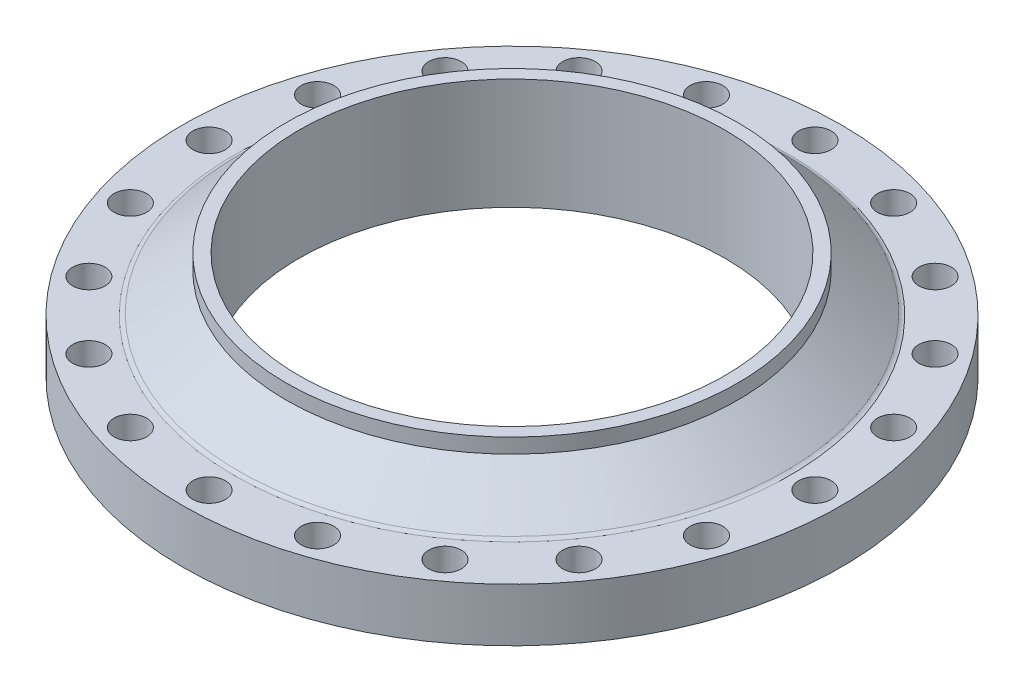
SolidWorks part; units mm, degrees
ref_plane "Front Plane" through (0, 0, 0) normal (0, 0, 1) x (1, 0, 0)
ref_plane "Top Plane" through (0, 0, 0) normal (0, 1, 0) x (1, 0, 0)
ref_plane "Right Plane" through (0, 0, 0) normal (1, 0, 0) x (0, 0, -1)
sketch "Sketch1" plane through (0, 0, 0) normal (0, 0, 1) x (1, 0, 0)
  line L0 (0, 92.0971) -> (0, -93.3251) construction
  line L1 (287.4, 0) -> (370, 0)
  line L2 (370, 0) -> (375, 5)
  line L3 (375, 5) -> (445, 5)
  line L4 (445, 5) -> (445, 77)
  line L5 (445, 77) -> (375, 77)
  line L6 (0, 92.0971) -> (0, 282.9763) construction
  line L7 (287.4, 0) -> (287.4, 150)
  line L9 (287.4, 150) -> (304.8, 150)
  line L10 (304.8, 150) -> (304.8, 130)
  line L11 (375, 77) -> (376.7318, 88.8744)
  line L12 (304.8, 130) -> (369.3298, 79.4292)
  arc A1 (375, 77) -> (369.3298, 79.4292) centre (376.7318, 88.8744) cw
  dimension "D1" = 150
  dimension "D2" = 72
  dimension "D3" = 5
  dimension "D4" = 17.4
  dimension "D5" = 20
  dimension "D7" = 12
revolve "Revolve2" add sketch "Sketch1" angle 360 about L6
sketch "Sketch2" plane through (0, 0, 0) normal (0, 1, 0) x (1, 0, 0)
  line L1 (0, 0) -> (409, 0) construction
  circle A0 centre (409, 0) radius 22
  circle A1 centre (388.9821, -126.388) radius 22
  circle A2 centre (330.888, -240.4042) radius 22
  circle A3 centre (240.4042, -330.888) radius 22
  circle A4 centre (126.388, -388.9821) radius 22
  circle A5 centre (0, -409) radius 22
  circle A6 centre (-126.388, -388.9821) radius 22
  circle A7 centre (-240.4042, -330.888) radius 22
  circle A8 centre (-330.888, -240.4042) radius 22
  circle A9 centre (-388.9821, -126.388) radius 22
  circle A10 centre (-409, 0) radius 22
  circle A11 centre (-388.9821, 126.388) radius 22
  circle A12 centre (-330.888, 240.4042) radius 22
  circle A13 centre (-240.4042, 330.888) radius 22
  circle A14 centre (-126.388, 388.9821) radius 22
  circle A15 centre (0, 409) radius 22
  circle A16 centre (126.388, 388.9821) radius 22
  circle A17 centre (240.4042, 330.888) radius 22
  circle A18 centre (330.888, 240.4042) radius 22
  circle A19 centre (388.9821, 126.388) radius 22
  dimension "D2" = 44
  dimension "D4" = 409
  dimension "D3" = 20
extrude "Cut-Extrude2" cut sketch "Sketch2" against normal mid plane 540
